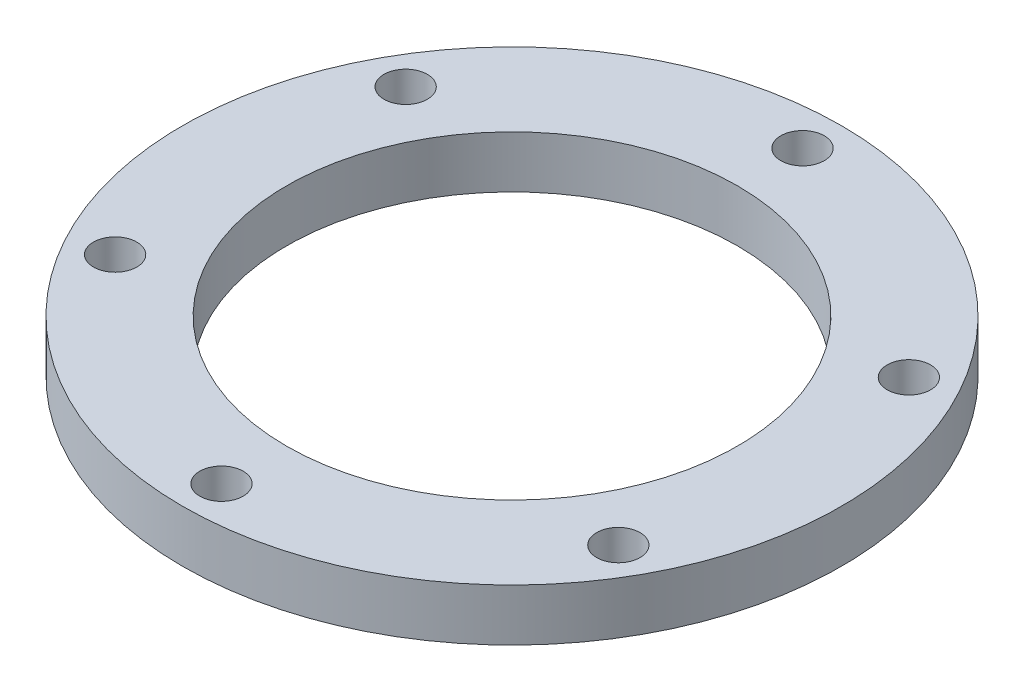
SolidWorks part; units mm, degrees
ref_plane "Front Plane" through (0, 0, 0) normal (0, 0, 1) x (1, 0, 0)
ref_plane "Top Plane" through (0, 0, 0) normal (0, 1, 0) x (1, 0, 0)
ref_plane "Right Plane" through (0, 0, 0) normal (1, 0, 0) x (0, 0, -1)
sketch "Sketch1" plane through (0, 0, 0) normal (0, 1, 0) x (1, 0, 0)
  line L0 (0, 39.37) -> (0, 33.02) construction
  line L1 (0, 45.72) -> (0, 48.26) construction
  circle A0 centre (0, 0) radius 48.26
  circle A1 centre (0, 0) radius 33.02
  circle A2 centre (0, 42.545) radius 3.175
  circle A3 centre (36.8451, 21.2725) radius 3.175
  circle A4 centre (36.8451, -21.2725) radius 3.175
  circle A5 centre (0, -42.545) radius 3.175
  circle A6 centre (-36.8451, -21.2725) radius 3.175
  circle A7 centre (-36.8451, 21.2725) radius 3.175
  dimension "D1" = 96.52
  dimension "D2" = 66.04
  dimension "D3" = 6.35
  dimension "D5" = 6.35
  dimension "D4" = 6
extrude "Boss-Extrude1" add sketch "Sketch1" along normal blind 7.62
